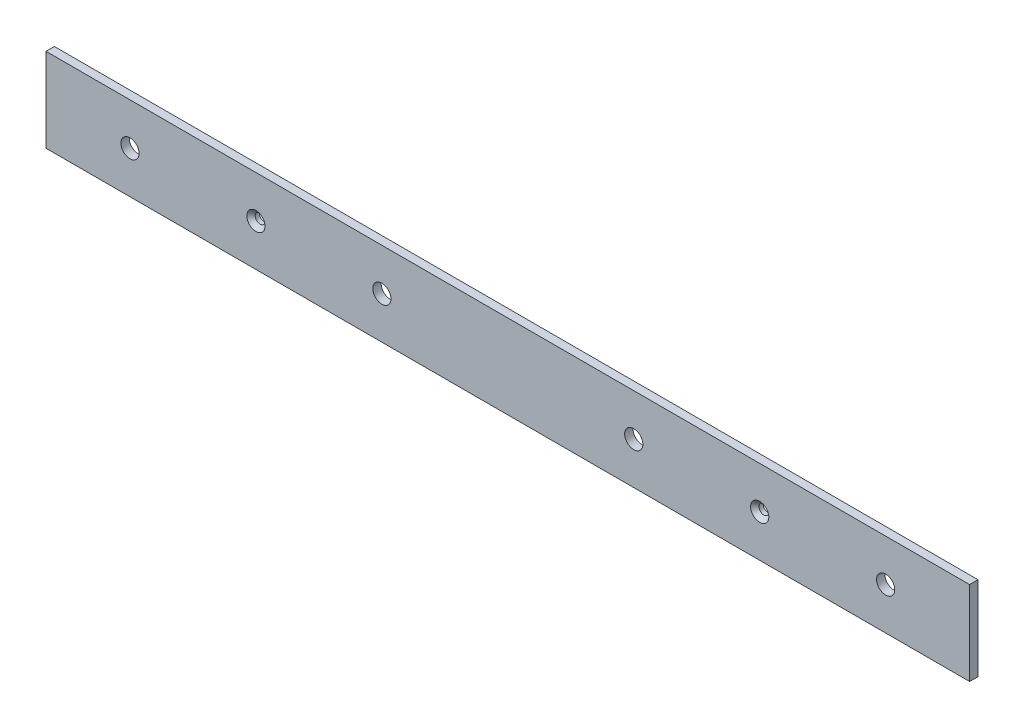
SolidWorks part; units mm, degrees
ref_plane "Спереди" through (0, 0, 0) normal (0, 0, 1) x (1, 0, 0)
ref_plane "Сверху" through (0, 0, 0) normal (0, 1, 0) x (1, 0, 0)
ref_plane "Справа" through (0, 0, 0) normal (1, 0, 0) x (0, 0, -1)
sketch "Эскиз1" plane through (0, 0, 0) normal (0, 0, 1) x (1, 0, 0)
  line L0 (0, 0) -> (0, 47.5203) construction
  line L1 (0, 0) -> (181.5318, 0) construction
  line L3 (-165, -15) -> (165, -15)
  line L4 (-165, -15) -> (-165, 15)
  line L5 (-165, 15) -> (165, 15)
  line L6 (165, -15) -> (165, 15)
  circle A0 centre (135, 0) radius 3.25
  circle A1 centre (90, 0) radius 1.75
  circle A2 centre (45, 0) radius 3.25
  circle A3 centre (-45, 0) radius 3.25
  circle A4 centre (-90, 0) radius 1.75
  circle A5 centre (-135, 0) radius 3.25
  dimension "D3" = 6.5
  dimension "D4" = 30
  dimension "D5" = 45
  dimension "D6" = 45
  dimension "D7" = 3.5
  dimension "D1" = 330
  dimension "D2" = 30
extrude "Вытянуть1" add sketch "Эскиз1" along normal blind 3
chamfer "Фаска1" distance 1.5 angle 45 2 edges at (-91.75, 0, 3) (91.75, 0, 3)
